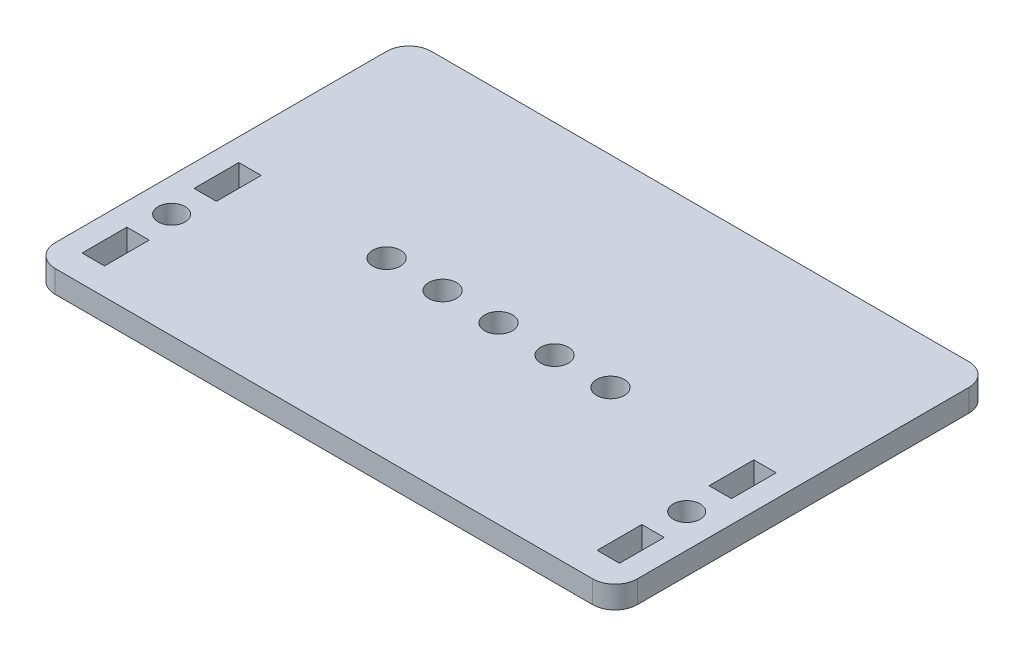
SolidWorks part; units mm, degrees
ref_plane "Front Plane" through (0, 0, 0) normal (0, 0, 1) x (1, 0, 0)
ref_plane "Top Plane" through (0, 0, 0) normal (0, 1, 0) x (1, 0, 0)
ref_plane "Right Plane" through (0, 0, 0) normal (1, 0, 0) x (0, 0, -1)
sketch "Sketch1" plane through (0, 0, 0) normal (0, 1, 0) x (1, 0, 0)
  line L1 (-65, 26) -> (65, 26)
  line L2 (-65, 26) -> (-65, -26)
  line L3 (-65, -26) -> (65, -26)
  line L4 (65, 26) -> (65, -26)
  line L5 (-65, 26) -> (65, -26) construction
  line L6 (-65, -26) -> (65, 26) construction
  point P0 (0, 0)
  dimension "D1" = 130
  dimension "D2" = 52
extrude "Boss-Extrude1" add sketch "Sketch1" along normal blind 5
sketch "Sketch2" plane through (0, 0, -26) normal (0, 0, -1) x (-1, 0, 0)
  line L4 (-65, 0) -> (65, 0)
  line L5 (65, 0) -> (65, 5)
  line L6 (65, 5) -> (-65, 5)
  line L7 (-65, 5) -> (-65, 0)
  line L8 (-65, 0) -> (65, 0)
  line L9 (65, 0) -> (65, 5)
  line L10 (65, 5) -> (-65, 5)
  line L11 (-65, 5) -> (-65, 0)
  dimension "D1" = 0
extrude "Boss-Extrude2" add sketch "Sketch2" along normal blind 32
sketch "Sketch3" plane through (0, 5, 0) normal (0, 1, 0) x (1, 0, 0)
  line L0 (-57.5, -10) -> (-57.5, 5) construction
  line L1 (0, 50.5) -> (0, -18.5) construction
  line L2 (57.5, -10) -> (57.5, 5) construction
  line L3 (55, 15) -> (55, 5)
  line L4 (-55, 10) -> (-60, 10) construction
  line L5 (-60, -10) -> (-55, -10)
  line L6 (-60, -10) -> (-60, -20)
  line L7 (-60, -20) -> (-55, -20)
  line L8 (57.5, -18.5) -> (57.5, 50.5)
  line L9 (57.5, 50.5) -> (-57.5, 50.5)
  line L10 (-57.5, 50.5) -> (-57.5, -18.5)
  line L11 (-57.5, -18.5) -> (57.5, -18.5)
  line L12 (57.5, -18.5) -> (57.5, 50.5) construction
  line L13 (57.5, 50.5) -> (-57.5, 50.5) construction
  line L14 (-57.5, 50.5) -> (-57.5, -18.5) construction
  line L15 (-57.5, -18.5) -> (57.5, -18.5) construction
  line L16 (-55, -10) -> (-55, -20)
  line L17 (60, 5) -> (55, 5)
  line L18 (-60, 15) -> (-55, 15)
  line L19 (-60, 15) -> (-60, 5)
  line L20 (-60, 5) -> (-55, 5)
  line L21 (-55, 15) -> (-55, 5)
  line L22 (60, 15) -> (60, 5)
  line L23 (60, 15) -> (55, 15)
  line L24 (55, -10) -> (55, -20)
  line L25 (60, -20) -> (55, -20)
  line L26 (60, -10) -> (60, -20)
  line L27 (60, -10) -> (55, -10)
  line L28 (-65, -26) -> (65, -26) construction
  circle A0 centre (-57.5, -2.5) radius 3
  circle A1 centre (57.5, -2.5) radius 3
  dimension "D6" = 6
  dimension "D1" = 7.5
  dimension "D2" = 10
  dimension "D3" = 5
  dimension "D4" = 6
  dimension "D5" = 35
extrude "Cut-Extrude1" cut sketch "Sketch3" against normal blind 10
fillet "Fillet1" radius 5 4 edges at (65, 2.5, -58) (-65, 2.5, 26) (65, 2.5, 26) (-65, 2.5, -58)
sketch "Sketch4" plane through (0, 5, 0) normal (0, 1, 0) x (1, 0, 0)
  line L1 (0, 58) -> (0, -26) construction
  line L2 (-60, 58) -> (60, 58) construction
  line L3 (-60, -26) -> (60, -26) construction
  circle A0 centre (-12.5, 13) radius 3.1
  circle A1 centre (-25.4, 44.5) radius 2.15 construction
  circle A2 centre (-12.7, 44.5) radius 2.15 construction
  circle A3 centre (0, 44.5) radius 2.15 construction
  circle A4 centre (12.7, 44.5) radius 2.15 construction
  circle A5 centre (25.4, 44.5) radius 2.15 construction
  circle A6 centre (-25, 13) radius 3.1
  circle A7 centre (0, 13) radius 3.1
  circle A8 centre (12.5, 13) radius 3.1
  circle A9 centre (25, 13) radius 3.1
  dimension "D1" = 31.5
  dimension "D2" = 4.3
  dimension "D3" = 13.5
  dimension "D4" = 12.7
  dimension "D5" = 12.7
  dimension "D6" = 6.2
  dimension "D7" = 12.5
  dimension "D8" = 12.5
extrude "Cut-Extrude2" cut sketch "Sketch4" against normal up to next
